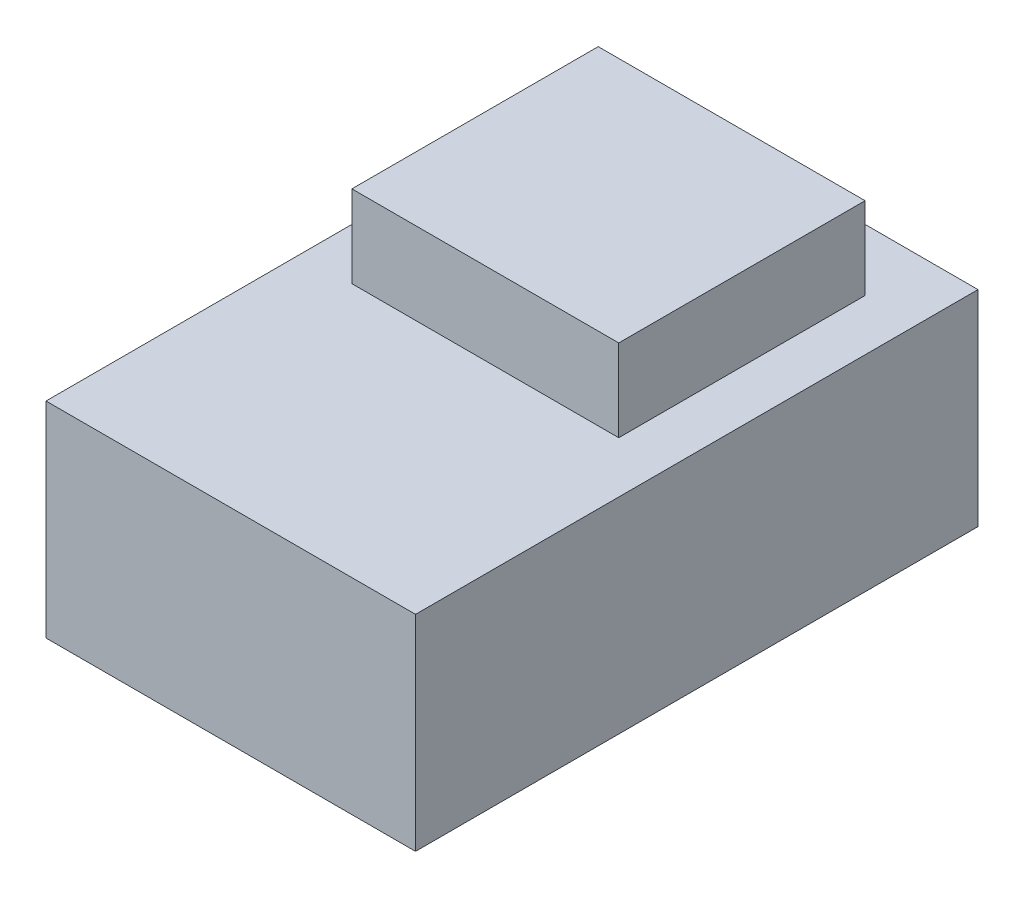
SolidWorks part; units mm, degrees
ref_plane "Ebene vorne" through (0, 0, 0) normal (0, 0, 1) x (1, 0, 0)
ref_plane "Ebene oben" through (0, 0, 0) normal (0, 1, 0) x (1, 0, 0)
ref_plane "Ebene rechts" through (0, 0, 0) normal (1, 0, 0) x (0, 0, -1)
sketch "Skizze1" plane through (0, 0, 0) normal (0, 0, 1) x (1, 0, 0)
  line L1 (-45, -25) -> (45, -25)
  line L2 (-45, -25) -> (-45, 25)
  line L3 (-45, 25) -> (45, 25)
  line L4 (45, -25) -> (45, 25)
  line L5 (-45, -25) -> (45, 25) construction
  line L6 (-45, 25) -> (45, -25) construction
  point P0 (0, 0)
  dimension "D1" = 90
  dimension "D2" = 50
extrude "Aufsatz-Linear austragen1" add sketch "Skizze1" along normal blind 137
sketch "Skizze2" plane through (0, 25, 0) normal (0, 1, 0) x (1, 0, 0)
  line L0 (45, 0) -> (-45, 0) construction
  line L1 (-32.5, -15) -> (32.5, -15)
  line L2 (-32.5, -15) -> (-32.5, -75)
  line L3 (-32.5, -75) -> (32.5, -75)
  line L4 (32.5, -15) -> (32.5, -75)
  line L5 (-32.5, -15) -> (32.5, -75) construction
  line L6 (-32.5, -75) -> (32.5, -15) construction
  point P0 (0, -45)
  point P7 (0, 0)
  dimension "D1" = 15
  dimension "D2" = 60
  dimension "D3" = 65
extrude "Aufsatz-Linear austragen2" add sketch "Skizze2" along normal blind 20
